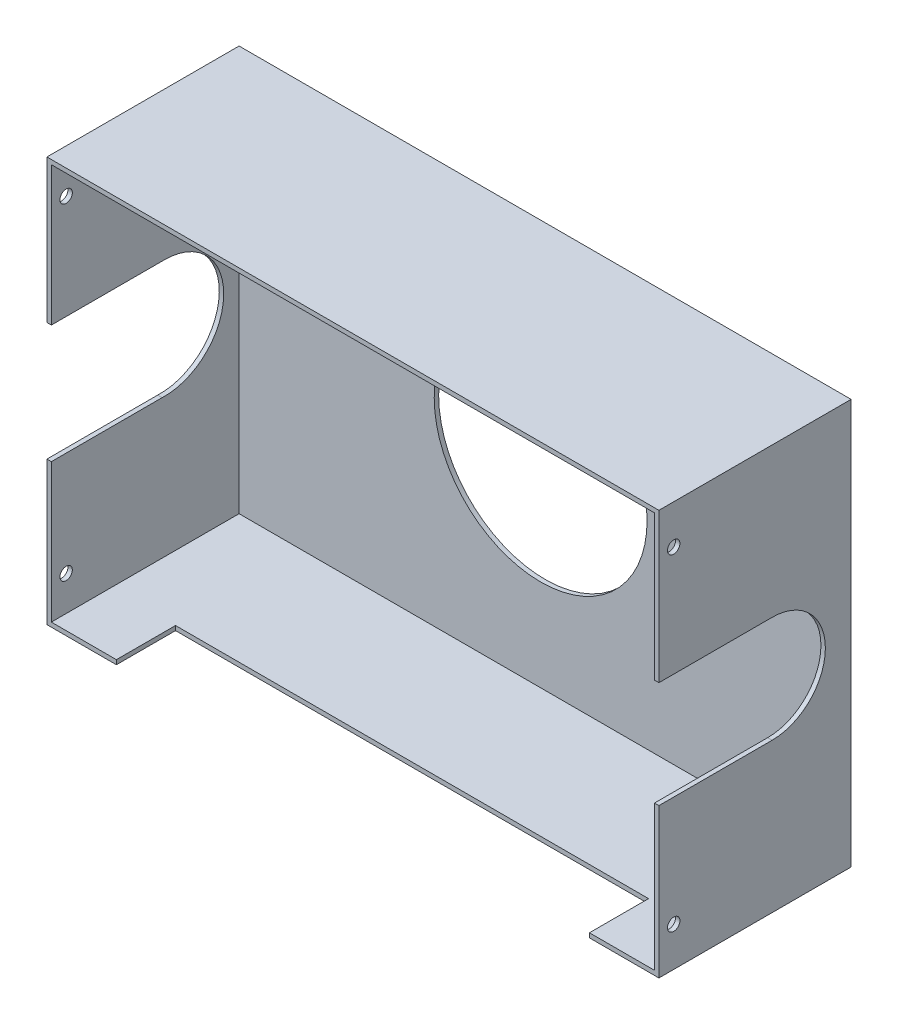
SolidWorks part; units mm, degrees
ref_plane "前视基准面" through (0, 0, 0) normal (0, 0, 1) x (1, 0, 0)
ref_plane "上视基准面" through (0, 0, 0) normal (0, 1, 0) x (1, 0, 0)
ref_plane "右视基准面" through (0, 0, 0) normal (1, 0, 0) x (0, 0, -1)
sketch "草图1" plane through (0, 0, 0) normal (0, 0, 1) x (1, 0, 0)
  line L1 (-103.5, 68.5) -> (103.5, 68.5)
  line L2 (-103.5, 68.5) -> (-103.5, -68.5)
  line L3 (-103.5, -68.5) -> (103.5, -68.5)
  line L4 (103.5, 68.5) -> (103.5, -68.5)
  line L5 (-103.5, 68.5) -> (103.5, -68.5) construction
  line L6 (-103.5, -68.5) -> (103.5, 68.5) construction
  point P0 (0, 0)
  dimension "D1" = 137
  dimension "D2" = 207
extrude "凸台-拉伸1" add sketch "草图1" along normal blind 65
shell "抽壳1" thickness 1.5
sketch "草图2" plane through (0, 0, 0) normal (0, 0, -1) x (-1, 0, 0)
  circle A0 centre (0, 0) radius 36
  dimension "D1" = 72
extrude "切除-拉伸1" cut sketch "草图2" against normal blind 80
sketch "草图4" plane through (103.5, 0, 0) normal (1, 0, 0) x (0, 0, -1)
  line L0 (0, -68.5) -> (0, 68.5) construction
  line L1 (-26.7, 18) -> (-65, 18)
  line L2 (-65, -68.5) -> (-65, 68.5) construction
  line L3 (-65, 18) -> (-65, -18)
  line L4 (-65, -18) -> (-26.7, -18)
  arc A0 (-26.7, -18) -> (-26.7, 18) centre (-26.7, 0) ccw
  dimension "D1" = 36
  dimension "D2" = 26.7
extrude "切除-拉伸2" cut sketch "草图4" against normal up to next
sketch "草图5" plane through (-103.5, 0, 0) normal (-1, 0, 0) x (0, 0, 1)
  line L0 (0, 68.5) -> (0, -68.5) construction
  line L1 (26.7, 20) -> (65, 20)
  line L2 (65, 68.5) -> (65, -68.5) construction
  line L3 (65, 20) -> (65, -20)
  line L4 (65, -20) -> (27.5414, -19.9823)
  arc A0 (26.7, 20) -> (27.5414, -19.9823) centre (26.7, 0) ccw
  dimension "D2" = 40
  dimension "D1" = 26.7
extrude "切除-拉伸3" cut sketch "草图5" against normal up to next and the other way through all
hole_wizard "M5 螺纹槽口的螺纹槽口钻头3" positions "草图7" profile "草图8" size "M5" standard "GB" slot yes end condition through all
sketch "草图7" plane through (-103.5, 0, 0) normal (-1, 0, 0) x (0, 0, 1)
  line L0 (65, 68.5) -> (0, 68.5) construction
  line L1 (65, -68.5) -> (0, -68.5) construction
  line L2 (65, -20) -> (65, -68.5) construction
  line L3 (65, 68.5) -> (65, 20) construction
  point P0 (60, 55.25)
  point P2 (60, -55.25)
  dimension "D1" = 13.25
  dimension "D2" = 13.25
  dimension "D3" = 5
  dimension "D4" = 5
sketch "草图8" plane through (-103.5, 55.25, 60) normal (0, 1, 0) x (0, 0, 1)
  line L0 (0, 0) -> (0, 207)
  line L1 (0, 207) -> (2.1, 207)
  line L2 (2.1, 207) -> (2.1, 0)
  line L5 (2.1, 0) -> (0, 0)
  line L11 (0, -6.35) -> (0, 107.95) construction
  dimension "通孔孔直径" = 4.2
  dimension "通孔孔深度" = 207
sketch "草图6" plane through (0, -68.5, 0) normal (0, -1, 0) x (1, 0, 0)
  line L0 (-103.5, 65) -> (103.5, 65) construction
  line L1 (-80, 65) -> (80, 65)
  line L2 (-80, 65) -> (-80, 45)
  line L3 (-80, 45) -> (80, 45)
  line L4 (80, 65) -> (80, 45)
  line L5 (-103.5, 65) -> (-103.5, 0) construction
  line L6 (103.5, 65) -> (103.5, 0) construction
  dimension "D1" = 160
  dimension "D2" = 20
  dimension "D3" = 23.5
  dimension "D4" = 23.5
extrude "切除-拉伸4" cut sketch "草图6" against normal up to next
